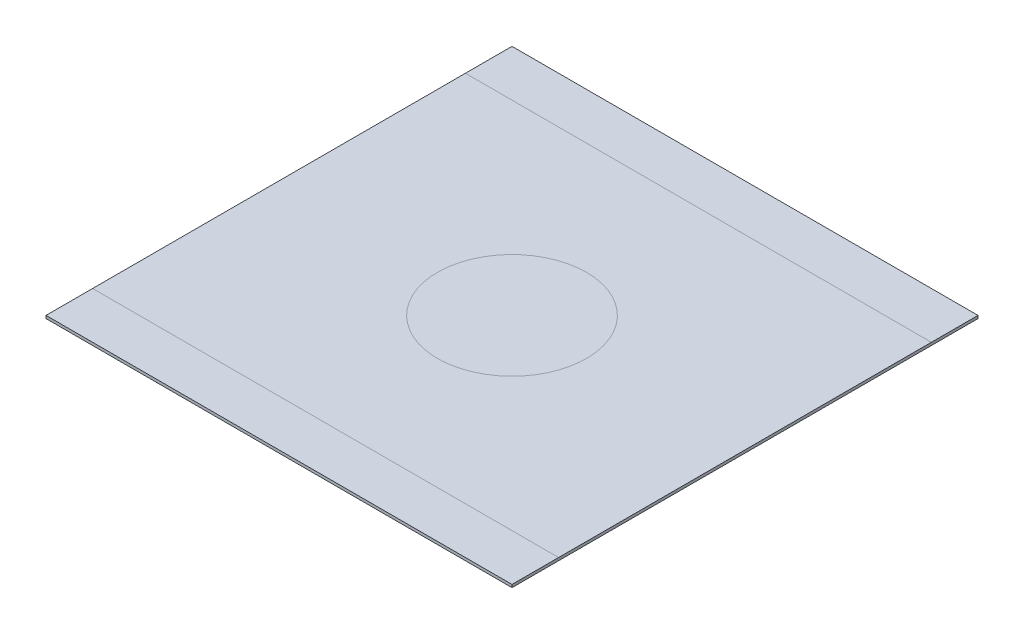
SolidWorks part; units mm, degrees
material "99.5% Aluminum Oxide"
ref_plane "Front Plane" through (0, 0, 0) normal (0, 0, 1) x (1, 0, 0)
ref_plane "Top Plane" through (0, 0, 0) normal (0, 1, 0) x (1, 0, 0)
ref_plane "Right Plane" through (0, 0, 0) normal (1, 0, 0) x (0, 0, -1)
sketch "Sketch1" plane through (0, 0, 0) normal (0, 1, 0) x (1, 0, 0)
  line L1 (-125, -125) -> (125, -125)
  line L2 (-125, -125) -> (-125, 125)
  line L3 (-125, 125) -> (125, 125)
  line L4 (125, -125) -> (125, 125)
  line L5 (-125, -125) -> (125, 125) construction
  line L6 (-125, 125) -> (125, -125) construction
  point P0 (0, 0)
  dimension "D1" = 250
extrude "Boss-Extrude1" add sketch "Sketch1" along normal mid plane 1.5
sketch "Sketch2" plane through (0, 0.75, 0) normal (0, 1, 0) x (1, 0, 0)
  line L0 (-125, 125) -> (-125, -125) construction
  line L1 (-125, -100) -> (125, -100)
  line L2 (-125, -100) -> (-125, -125)
  line L3 (-125, -125) -> (125, -125)
  line L4 (125, -100) -> (125, -125)
  line L5 (125, -125) -> (125, 125) construction
  line L6 (-125, 125) -> (125, 125)
  line L7 (-125, 125) -> (-125, 100)
  line L8 (-125, 100) -> (125, 100)
  line L9 (125, 125) -> (125, 100)
  dimension "D1" = 25
split line "Split Line1"
sketch "Sketch3" plane through (0, 0.75, 0) normal (0, 1, 0) x (1, 0, 0)
  circle A0 centre (0, 0) radius 40
  dimension "D1" = 80
split line "Split Line2"
